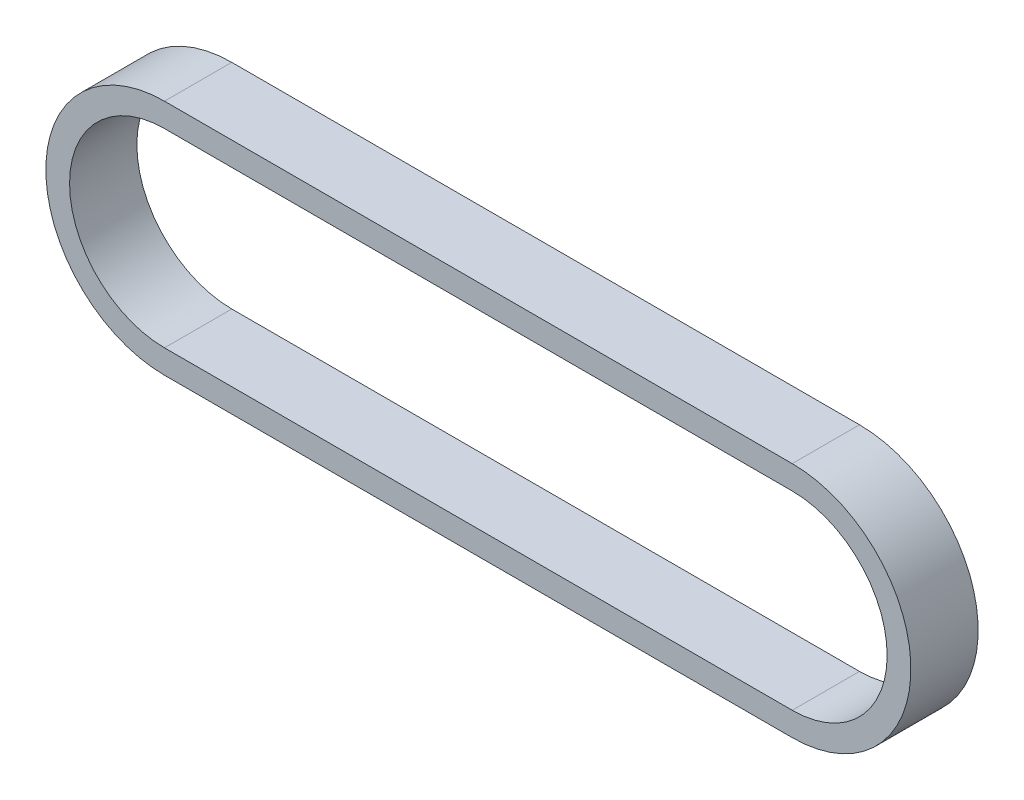
SolidWorks part; units mm, degrees
material "Silicon Rubber"
ref_plane "Front Plane" through (0, 0, 0) normal (0, 0, 1) x (1, 0, 0)
ref_plane "Top Plane" through (0, 0, 0) normal (0, 1, 0) x (1, 0, 0)
ref_plane "Right Plane" through (0, 0, 0) normal (1, 0, 0) x (0, 0, -1)
sketch "Sketch1" plane through (0, 0, 0) normal (0, 0, 1) x (1, 0, 0)
  line L0 (0, 0) -> (83.975, 0) construction
  line L1 (0, 12.7) -> (83.975, 12.7)
  line L2 (0, -12.7) -> (83.975, -12.7)
  line L3 (0, 0) -> (83.975, 0) construction
  line L4 (0, 15.875) -> (83.975, 15.875)
  line L5 (0, -15.875) -> (83.975, -15.875)
  arc A0 (0, 12.7) -> (0, -12.7) centre (0, 0) ccw
  arc A1 (83.975, -12.7) -> (83.975, 12.7) centre (83.975, 0) ccw
  arc A2 (0, 15.875) -> (0, -15.875) centre (0, 0) ccw
  arc A3 (83.975, -15.875) -> (83.975, 15.875) centre (83.975, 0) ccw
  point P3 (41.9875, 0)
  point P8 (41.9875, 0)
  dimension "D2" = 15.875
  dimension "D3" = 3.175
  dimension "D1" = 83.975
extrude "Boss-Extrude1" add sketch "Sketch1" along normal blind 9
